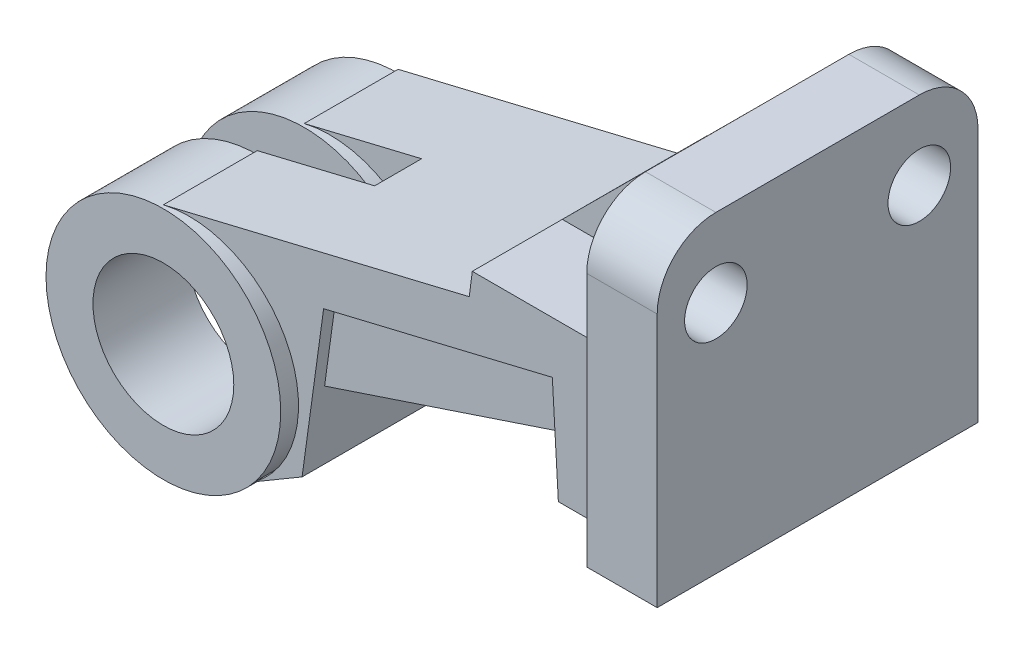
SolidWorks part; units mm, degrees
ref_plane "Front Plane" through (0, 0, 0) normal (0, 0, 1) x (1, 0, 0)
ref_plane "Top Plane" through (0, 0, 0) normal (0, 1, 0) x (1, 0, 0)
ref_plane "Right Plane" through (0, 0, 0) normal (1, 0, 0) x (0, 0, -1)
sketch "Sketch1" plane through (0, 0, 0) normal (0, 0, 1) x (1, 0, 0)
  line L0 (23.4539, -18.706) -> (35.4539, -11.659)
  line L1 (35.4539, -11.659) -> (40.9626, 28.341)
  line L2 (40.9626, 28.341) -> (99.4189, 42.3689)
  line L3 (99.4189, 42.3689) -> (100.9626, 15.6149)
  line L4 (100.9626, 15.6149) -> (118.9626, 15.6149)
  line L5 (118.9626, 15.6149) -> (118.9626, 55.6149)
  line L6 (118.9626, 55.6149) -> (78.9626, 55.6149)
  line L7 (78.9626, 55.6149) -> (78.1885, 49.6149)
  line L8 (78.1885, 49.6149) -> (0, 30.8517)
  circle A0 centre (0, 0) radius 30
  circle A1 centre (0, 0) radius 18
  arc A2 (0, 30.8517) -> (23.4539, -18.706) centre (6.5358, 3.6161) cw
  dimension "D1" = 60
  dimension "D2" = 36
  dimension "D3" = 60
  dimension "D4" = 6
  dimension "D5" = 40
  dimension "D6" = 12
  dimension "D7" = 40
  dimension "D9" = 12
  dimension "D10" = 40
  dimension "D11" = 18
extrude "Boss-Extrude1" add sketch "Sketch1" against normal blind 60 contours L8 A2 L0 L1 L2 L3 L4 L5 L6 L7 | A0 A1
ref_plane "Plane1" through (119, 0, 0) normal (1, 0, 0) x (0, 0, -1)
sketch "Sketch2" plane through (119, 0, 0) normal (1, 0, 0) x (0, 0, -1)
  line L5 (-10.7756, 15.561) -> (71.2244, 15.561)
  line L6 (-10.7756, 15.561) -> (-10.7756, 95.561)
  line L7 (-10.7756, 95.561) -> (71.2244, 95.561)
  line L8 (71.2244, 15.561) -> (71.2244, 95.561)
  point P0 (30.3732, 44.7077)
  point P5 (-9.4485, 16.2389)
  point P6 (71.2244, 15.561)
  dimension "D1" = 80
  dimension "D2" = 82
extrude "Boss-Extrude2" add sketch "Sketch2" along normal blind 18 separate body
fillet "Fillet1" radius 15 2 edges at (128, 95.561, -71.2244) (128, 95.561, 10.7756)
ref_plane "Plane2" through (0, 0, -29) normal (0, 0, 1) x (1, 0, 0)
sketch "Sketch3" plane through (0, 0, -29) normal (0, 0, 1) x (1, 0, 0)
  line L0 (119, 95.561) -> (78.9626, 55.6149)
  line L1 (78.9626, 55.6149) -> (118.9626, 55.6149)
  line L2 (118.9626, 55.6149) -> (119, 95.561)
extrude "Boss-Extrude3" add sketch "Sketch3" along normal mid plane 12
ref_plane "Plane3" through (30, 0, 0) normal (-1, 0, 0) x (0, 0, 1)
sketch "Sketch4" plane through (30, 0, 0) normal (-1, 0, 0) x (0, 0, 1)
  line L0 (-36, 46.6856) -> (-24, 46.6856)
  line L1 (-24, 46.6856) -> (-24, -35.1229)
  line L2 (-24, -35.1229) -> (-36, -35.1229)
  line L3 (-36, -35.1229) -> (-36, 46.6856)
  line L4 (0, -30) -> (0, 30) construction
  line L6 (-60, 30) -> (-60, -30) construction
  point P8 (-24, 46.6856)
  dimension "D1" = 24
  dimension "D2" = 24
extrude "Cut-Extrude1" cut sketch "Sketch4" along normal blind 62
sketch "Sketch9" plane through (119, 0, 0) normal (-1, 0, 0) x (0, 0, 1)
  line L0 (10.7756, 80.561) -> (10.7756, 15.561) construction
  line L1 (-71.2244, 15.561) -> (-71.2244, 80.561) construction
  line L2 (-56.2244, 95.561) -> (-4.2244, 95.561) construction
  circle A0 centre (-56.2244, 75.561) radius 8
  circle A1 centre (-4.2244, 75.561) radius 8
  dimension "D1" = 16
  dimension "D2" = 16
  dimension "D3" = 15
  dimension "D4" = 15
  dimension "D5" = 52
  dimension "D6" = 20
extrude "Cut-Extrude2" cut sketch "Sketch9" against normal blind 32
sketch "Sketch10" plane through (0, 0, -29) normal (0, 0, 1) x (1, 0, 0)
  line L0 (38.2083, 8.341) -> (100.1907, 28.9919)
  line L1 (35.4539, -11.659) -> (40.9626, 28.341) construction
  line L2 (99.4189, 42.3689) -> (100.9626, 15.6149) construction
  line L3 (100.1907, 28.9919) -> (99.4189, 42.3689)
  line L4 (99.4189, 42.3689) -> (40.9626, 28.341)
  line L5 (40.9626, 28.341) -> (38.2083, 8.341)
extrude "Boss-Extrude4" add sketch "Sketch10" along normal mid plane 52
